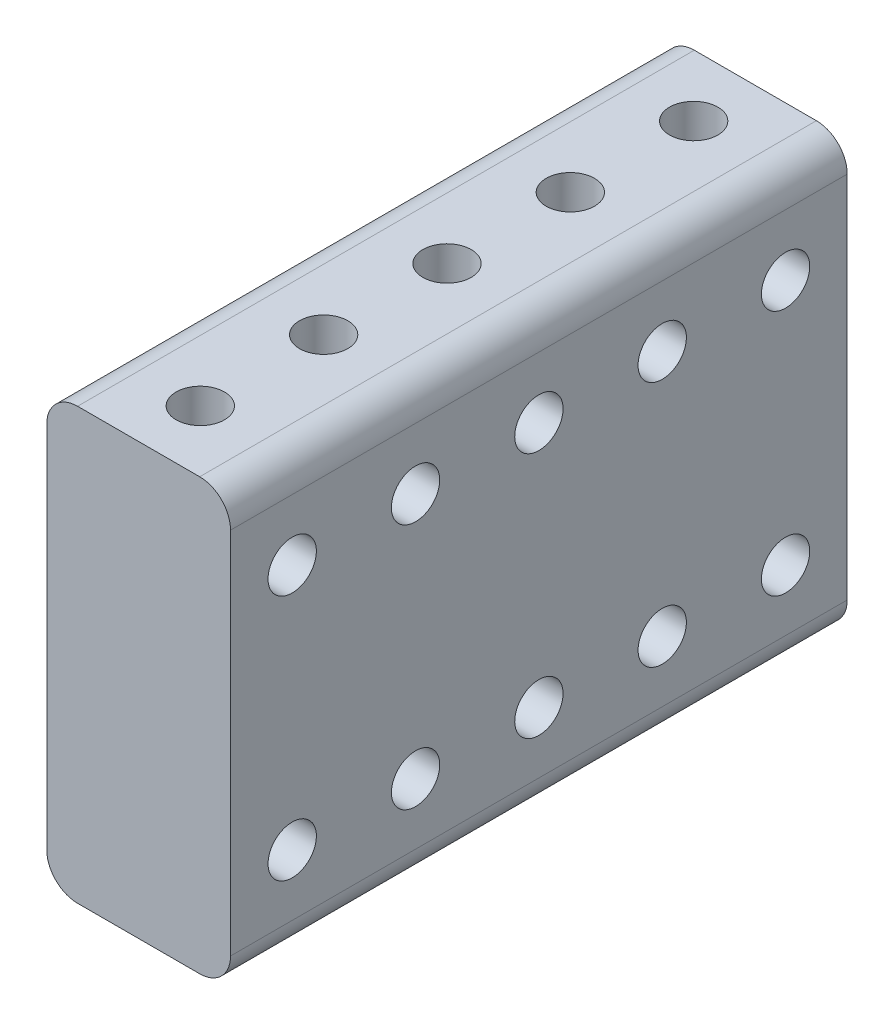
SolidWorks part; units mm, degrees
material "PET"
ref_plane "Front Plane" through (0, 0, 0) normal (0, 0, 1) x (1, 0, 0)
ref_plane "Top Plane" through (0, 0, 0) normal (0, 1, 0) x (1, 0, 0)
ref_plane "Right Plane" through (0, 0, 0) normal (1, 0, 0) x (0, 0, -1)
sketch "Sketch1" plane through (0, 0, 0) normal (0, 0, 1) x (1, 0, 0)
  line L1 (0, 0) -> (18.923, 0)
  line L2 (0, 0) -> (0, 44.323)
  line L3 (0, 44.323) -> (18.923, 44.323)
  line L4 (18.923, 0) -> (18.923, 44.323)
  dimension "D1" = 18.923
  dimension "D2" = 44.323
extrude "Boss-Extrude1" add sketch "Sketch1" along normal blind 63.5
fillet "Fillet1" radius 3.175 4 edges at (0, 44.323, 31.75) (18.923, 0, 31.75) (0, 0, 31.75) (18.923, 44.323, 31.75)
sketch "Sketch2" plane through (0, 44.323, 0) normal (0, 1, 0) x (1, 0, 0)
  line L0 (9.4615, 0) -> (9.4615, -63.5) construction
  line L1 (15.748, 0) -> (3.175, 0) construction
  line L2 (15.748, -63.5) -> (3.175, -63.5) construction
  circle A0 centre (9.4615, -6.35) radius 2.4892
  circle A1 centre (9.4615, -19.05) radius 2.4892
  circle A2 centre (9.4615, -31.75) radius 2.4892
  circle A3 centre (9.4615, -44.45) radius 2.4892
  circle A4 centre (9.4615, -57.15) radius 2.4892
  dimension "D1" = 4.9784
  dimension "D4" = 12.7
  dimension "D2" = 6.35
  dimension "D3" = 5
extrude "Cut-Extrude1" cut sketch "Sketch2" against normal blind 63.5
sketch "Sketch3" plane through (18.923, 0, 0) normal (1, 0, 0) x (0, 0, -1)
  line L0 (-63.5, 22.1615) -> (0, 22.1615) construction
  line L1 (-63.5, 3.175) -> (-63.5, 41.148) construction
  line L2 (0, 3.175) -> (0, 41.148) construction
  circle A0 centre (-57.15, 34.8615) radius 2.4892
  circle A1 centre (-44.45, 34.8615) radius 2.4892
  circle A2 centre (-31.75, 34.8615) radius 2.4892
  circle A3 centre (-19.05, 34.8615) radius 2.4892
  circle A4 centre (-6.35, 34.8615) radius 2.4892
  circle A5 centre (-44.45, 9.4615) radius 2.4892
  circle A6 centre (-31.75, 9.4615) radius 2.4892
  circle A7 centre (-19.05, 9.4615) radius 2.4892
  circle A8 centre (-6.35, 9.4615) radius 2.4892
  circle A9 centre (-57.15, 9.4615) radius 2.4892
  point P8 (-54.3224, 11.6119)
  dimension "D2" = 4.9784
  dimension "D3" = 6.35
  dimension "D1" = 12.7
  dimension "D6" = 25.4
  dimension "D7" = 12.7
  dimension "D4" = 5
  dimension "D5" = 2
extrude "Cut-Extrude2" cut sketch "Sketch3" against normal blind 63.5
